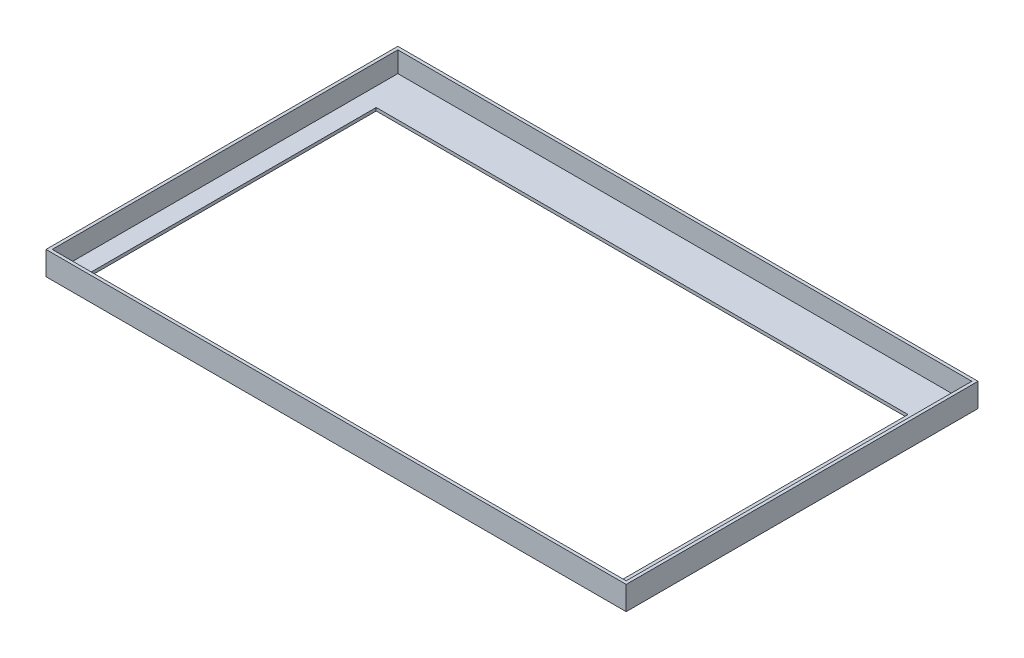
SolidWorks part; units mm, degrees
ref_plane "Front" through (0, 0, 0) normal (0, 0, 1) x (1, 0, 0)
ref_plane "Top" through (0, 0, 0) normal (0, 1, 0) x (1, 0, 0)
ref_plane "Right" through (0, 0, 0) normal (1, 0, 0) x (0, 0, -1)
sketch "Sketch1" plane through (0, 0, 0) normal (0, 1, 0) x (1, 0, 0)
  line L1 (0, 0) -> (282, 0)
  line L2 (0, 0) -> (0, -171)
  line L3 (0, -171) -> (282, -171)
  line L4 (282, 0) -> (282, -171)
  dimension "D1" = 282
  dimension "D2" = 171
extrude "Boss-Extrude1" add sketch "Sketch1" along normal blind 1.5
sketch "Sketch2" plane through (0, 1.5, 0) normal (0, 1, 0) x (1, 0, 0)
  line L0 (1.5, -169.5) -> (1.5, -1.5)
  line L1 (0, -171) -> (282, -171)
  line L2 (0, -171) -> (0, 0)
  line L3 (0, 0) -> (282, 0)
  line L4 (282, -171) -> (282, 0)
  line L5 (1.5, -1.5) -> (280.5, -1.5)
  line L6 (280.5, -169.5) -> (280.5, -1.5)
  line L7 (1.5, -169.5) -> (280.5, -169.5)
  dimension "D1" = 1.5
extrude "Boss-Extrude2" add sketch "Sketch2" along normal blind 10
sketch "Sketch3" plane through (0, 1.5, 0) normal (0, 1, 0) x (1, 0, 0)
  line L0 (280.5, -1.5) -> (1.5, -1.5) construction
  line L1 (10.5, -166) -> (269, -166)
  line L2 (10.5, -166) -> (10.5, -21)
  line L3 (10.5, -21) -> (269, -21)
  line L4 (269, -166) -> (269, -21)
  line L5 (1.5, -169.5) -> (280.5, -169.5) construction
  line L6 (280.5, -169.5) -> (280.5, -1.5) construction
  line L8 (1.5, -1.5) -> (1.5, -169.5) construction
  point P10 (0, 0)
  dimension "D1" = 19.5
  dimension "D2" = 3.5
  dimension "D3" = 11.5
  dimension "D4" = 9
extrude "Cut-Extrude1" cut sketch "Sketch3" against normal blind 10
